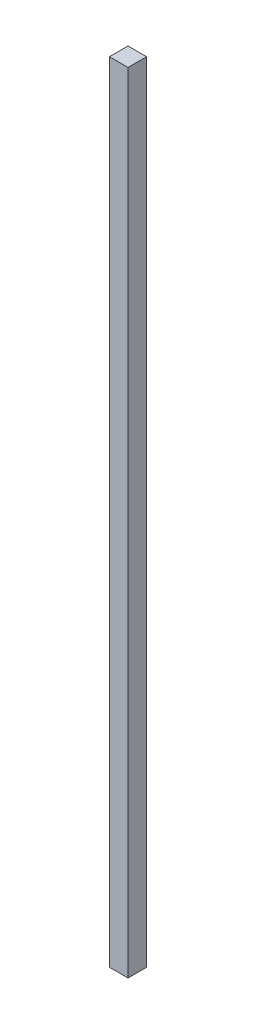
SolidWorks part; units mm, degrees
ref_plane "Front Plane" through (0, 0, 0) normal (0, 0, 1) x (1, 0, 0)
ref_plane "Top Plane" through (0, 0, 0) normal (0, 1, 0) x (1, 0, 0)
ref_plane "Right Plane" through (0, 0, 0) normal (1, 0, 0) x (0, 0, -1)
other "Configuration Table"
sketch "Sketch1" plane through (0, 0, 0) normal (0, 0, 1) x (1, 0, 0)
  line L1 (566, 640) -> (574, 640)
  line L2 (566, 640) -> (566, 980)
  line L3 (566, 980) -> (574, 980)
  line L4 (574, 640) -> (574, 980)
extrude "PACK_kapak_kolu_dikey_2_1" add sketch "Sketch1" against normal blind 8 from offset 596 separate body
